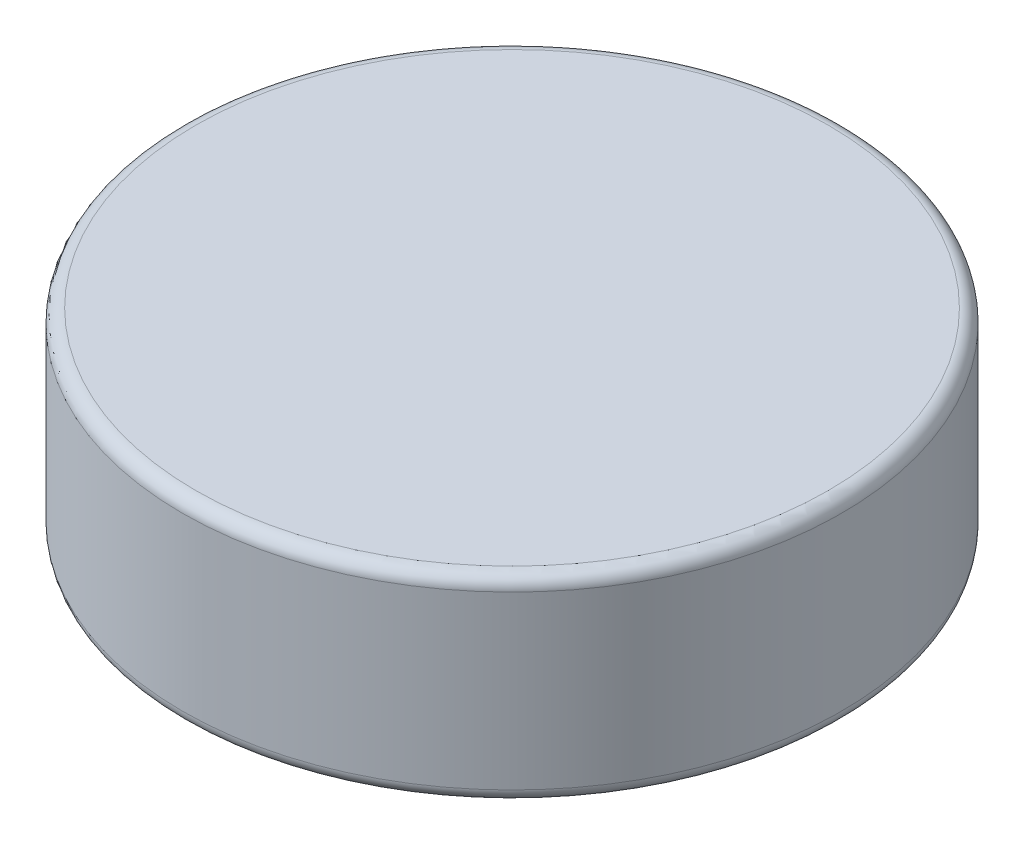
SolidWorks part; units mm, degrees
material "Chrome Stainless Steel"
ref_plane "Front Plane" through (0, 0, 0) normal (0, 0, 1) x (1, 0, 0)
ref_plane "Top Plane" through (0, 0, 0) normal (0, 1, 0) x (1, 0, 0)
ref_plane "Right Plane" through (0, 0, 0) normal (1, 0, 0) x (0, 0, -1)
sketch "Sketch1" plane through (0, 0, 0) normal (0, 1, 0) x (1, 0, 0)
  circle A0 centre (0, 0) radius 50
  dimension "D1" = 100
extrude "Boss-Extrude1" add sketch "Sketch1" along normal mid plane 30
fillet "Fillet1" radius 2 2 edges at (0, -15, 50) (0, 15, 50)
